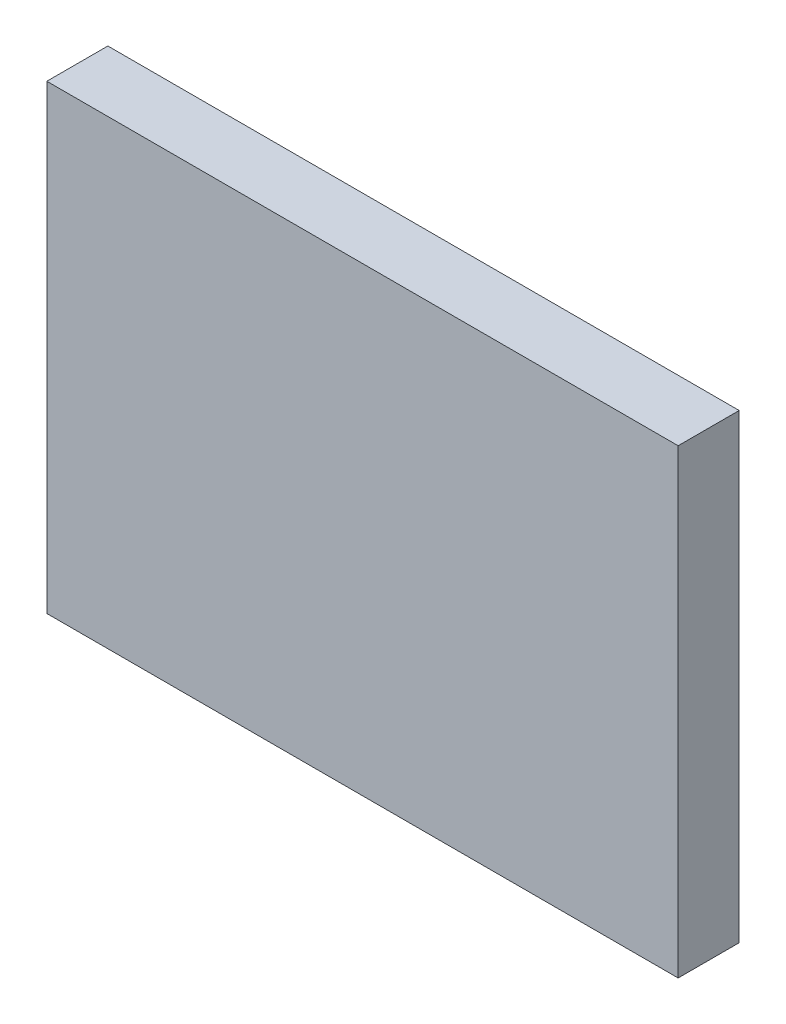
SolidWorks part; units mm, degrees
ref_plane "Front Plane" through (0, 0, 0) normal (0, 0, 1) x (1, 0, 0)
ref_plane "Top Plane" through (0, 0, 0) normal (0, 1, 0) x (1, 0, 0)
ref_plane "Right Plane" through (0, 0, 0) normal (1, 0, 0) x (0, 0, -1)
sketch "Sketch1" plane through (0, 0, 0) normal (0, 0, 1) x (1, 0, 0)
  line L1 (-43.6019, 39.5884) -> (59.8387, 39.5884)
  line L2 (-43.6019, 39.5884) -> (-43.6019, -35.9397)
  line L3 (-43.6019, -35.9397) -> (59.8387, -35.9397)
  line L4 (59.8387, 39.5884) -> (59.8387, -35.9397)
extrude "Boss-Extrude1" add sketch "Sketch1" along normal blind 10
